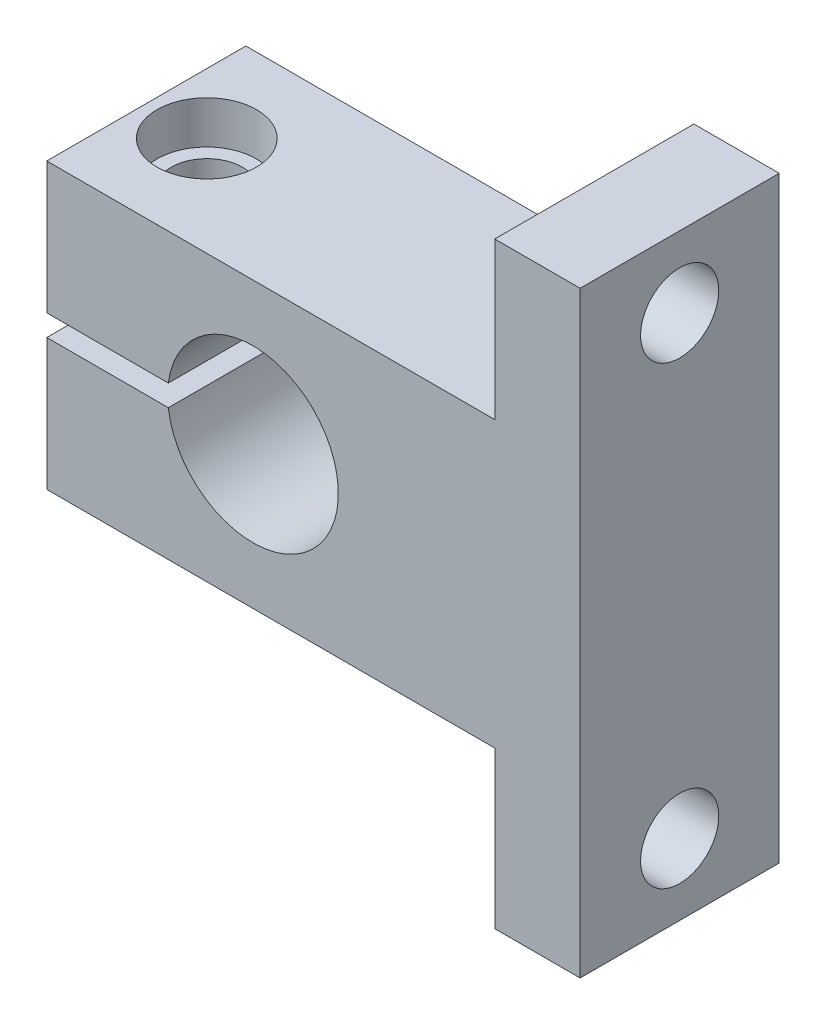
SolidWorks part; units mm, degrees
material "Liga 6061"
ref_plane "Plano frontal" through (0, 0, 0) normal (0, 0, 1) x (1, 0, 0)
ref_plane "Plano superior" through (0, 0, 0) normal (0, 1, 0) x (1, 0, 0)
ref_plane "Plano direito" through (0, 0, 0) normal (1, 0, 0) x (0, 0, -1)
sketch "Esboço1" plane through (0, 0, 0) normal (0, 0, 1) x (1, 0, 0)
  line L0 (0, 0) -> (0, 42)
  line L1 (0, 42) -> (-6, 42)
  line L2 (-6, 42) -> (-6, 31)
  line L3 (-6, 31) -> (-37.5, 31)
  line L4 (-37.5, 31) -> (-37.5, 21.75)
  line L5 (-37.5, 11) -> (-6, 11)
  line L6 (-6, 11) -> (-6, 0)
  line L7 (-6, 0) -> (0, 0)
  line L9 (-37.5, 21.75) -> (-28.9529, 21.75)
  line L11 (-37.5, 20.25) -> (-28.9529, 20.25)
  line L12 (-37.5, 20.25) -> (-37.5, 11)
  arc A0 (-28.9529, 20.25) -> (-28.9529, 21.75) centre (-23, 21) ccw
  dimension "D6" = 12
  dimension "D1" = 42
  dimension "D2" = 20
  dimension "D3" = 37.5
  dimension "D4" = 23
  dimension "D5" = 6
  dimension "D8" = 10
  dimension "D9" = 1.5
extrude "Extrusão1" add sketch "Esboço1" along normal blind 14
sketch "Esboço2" plane through (0, 31, 0) normal (0, 1, 0) x (1, 0, 0)
  line L0 (-37.5, -14) -> (-37.5, 0) construction
  line L1 (-28.9529, -14) -> (-37.5, -14) construction
  circle A0 centre (-33.25, -7) radius 2.5
  point P5 (-33.2265, -14)
  dimension "D1" = 5
  dimension "D2" = 4.25
  dimension "D3" = 7
extrude "Extrusão2" cut sketch "Esboço2" against normal up to next
hole_wizard "Furo roscado de M4x0.71" positions "3DSketch2" profile "Esboço4" tap size "M4x0.7" standard "Métrico Ansi"
sketch3d "3DSketch2"
  line L0 (-37.5, 20.25, 14) -> (-37.5, 20.25, 0) construction
  line L1 (-28.9529, 20.25, 0) -> (-37.5, 20.25, 0) construction
  point P0 (-33.25, 20.25, 7)
  dimension "D1" = 4.25
  dimension "D2" = 7
sketch "Esboço4" plane through (-33.25, 20.25, 7) normal (1, 0, 0) x (0, 0, 1)
  line L0 (0, 0) -> (0, 12.4914)
  line L1 (0, 12.4914) -> (1.65, 11.5)
  line L2 (1.65, 11.5) -> (1.65, 0)
  line L5 (1.65, 0) -> (0, 0)
  line L10 (0, 12.4914) -> (-1.65, 11.5) construction
  line L11 (0, -6.35) -> (0, 107.95) construction
  dimension "Tap Drill Dia." = 3.3
  dimension "Tap Drill Depth" = 11.5
  dimension "Drill Angle" = 118
cosmetic thread "Rosca de furo1" parameters "D1"=8, "D2"=4
sketch "Esboço5" plane through (-6, 0, 0) normal (-1, 0, 0) x (0, 0, 1)
  line L0 (14, 42) -> (0, 42) construction
  line L1 (0, 42) -> (0, 31) construction
  circle A0 centre (7, 37) radius 2.75
  circle A1 centre (7, 5) radius 2.75
  dimension "D1" = 5.5
  dimension "D2" = 5.5
  dimension "D3" = 5
  dimension "D4" = 7
  dimension "D5" = 5
  dimension "D6" = 7
extrude "Extrusão3" cut sketch "Esboço5" against normal through all
sketch "Esboço6" plane through (0, 31, 0) normal (0, 1, 0) x (1, 0, 0)
  circle A0 centre (-33.25, -7) radius 3.5
  dimension "D1" = 7
extrude "Extrusão4" cut sketch "Esboço6" against normal blind 3
